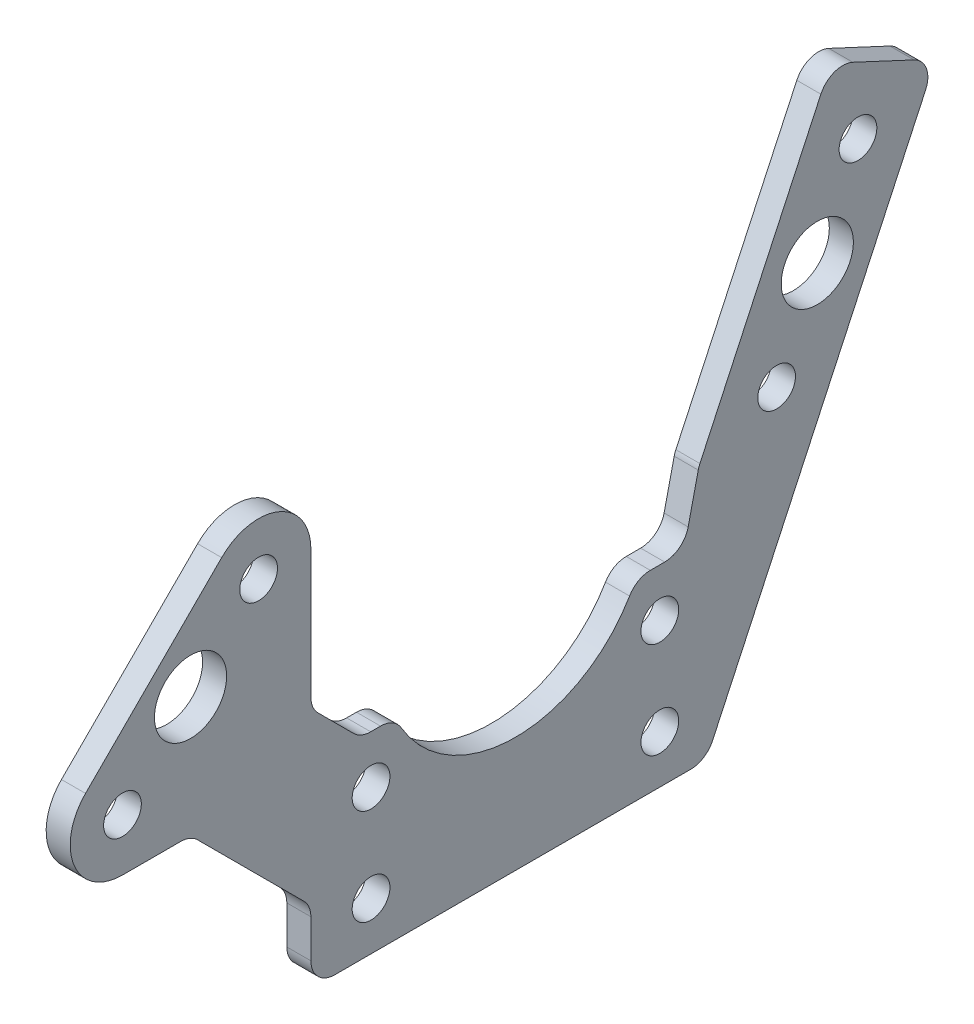
SolidWorks part; units mm, degrees
material "6061-T6 (SS)"
ref_plane "Front Plane" through (0, 0, 0) normal (0, 0, 1) x (1, 0, 0)
ref_plane "Top Plane" through (0, 0, 0) normal (0, 1, 0) x (1, 0, 0)
ref_plane "Right Plane" through (0, 0, 0) normal (1, 0, 0) x (0, 0, -1)
sketch "Sketch1" plane through (0, 0, 0) normal (1, 0, 0) x (0, 0, -1)
  line L1 (0, 0) -> (31.75, 0)
  line L2 (0, 0) -> (0, 31.75)
  line L3 (0, 31.75) -> (31.75, 31.75)
  line L4 (31.75, 0) -> (31.75, 31.75)
  line L8 (6.8947, 6.8947) -> (24.8553, 24.8553) construction
  line L13 (0, 9.7506) -> (21.9994, 31.75)
  line L14 (15.875, 0) -> (31.75, -15.875)
  line L15 (67.7946, 42.0544) -> (85.2585, 27.3883) construction
  line L16 (31.75, 0) -> (84.1375, 0)
  line L17 (31.75, 0) -> (31.75, -25.4)
  line L18 (31.75, -25.4) -> (84.1375, -25.4)
  line L19 (84.1375, 0) -> (84.1375, -25.4)
  line L20 (31.75, 6.5756) -> (38.3256, 0)
  circle A4 centre (39.6875, -6.35) radius 2.4892
  circle A5 centre (77.7875, -6.35) radius 2.4892
  circle A6 centre (39.6875, -19.05) radius 2.4892
  circle A7 centre (77.7875, -19.05) radius 2.4892
  circle A8 centre (15.875, 15.875) radius 4.7625
  arc A9 (42.8625, 0) -> (74.6125, 0) centre (58.7375, 7.2748) ccw
  circle A10 centre (6.8947, 6.8947) radius 2.4892
  circle A11 centre (24.8553, 24.8553) radius 2.4892
  arc A13 (2.0194, 11.7701) -> (6.8947, 0) centre (6.8947, 6.8947) ccw
  arc A14 (31.75, 24.8553) -> (19.9799, 29.7306) centre (24.8553, 24.8553) ccw
  arc A15 (6.8947, 0) -> (11.7701, 11.7701) centre (6.8947, 6.8947) ccw construction
  arc A16 (11.7701, 11.7701) -> (2.0194, 11.7701) centre (6.8947, 6.8947) ccw construction
  arc A17 (19.9799, 19.9799) -> (31.75, 24.8553) centre (24.8553, 24.8553) ccw construction
  arc A18 (19.9799, 29.7306) -> (19.9799, 19.9799) centre (24.8553, 24.8553) ccw construction
  point P8 (15.875, 15.875)
  point P10 (15.875, 31.75)
  point P11 (0, 15.875)
  dimension "D3" = 25.4
  dimension "D5" = 4.9784
  dimension "D10" = 9.525
  dimension "D13" = 17.4625
  dimension "D14" = 45
  dimension "D15" = 25.4
  dimension "D2" = 31.75
  dimension "D4" = 25.4
  dimension "D6" = 52.3875
  dimension "D7" = 6.35
  dimension "D8" = 45
  dimension "D9" = 7.9375
  dimension "D11" = 31.75
  dimension "D12" = 15.875
  dimension "D16" = 6.35
  dimension "D17" = 6.35
extrude "Boss-Extrude1" add sketch "Sketch1" along normal mid plane 3.175
fillet "Fillet1" radius 3.175 9 edges at (0, 6.5756, -31.75) (0, 0, -38.3256) (0, 0, -42.8625) (0, 0, -74.6125) (0, 0, -84.1375) (0, -25.4, -84.1375) (0, -25.4, -31.75) (0, -15.875, -31.75) (0, 0, -15.875)
sketch "Sketch2" plane through (1.5875, 0, 0) normal (1, 0, 0) x (0, 0, -1)
  line L0 (31.75, 50.8) -> (84.1375, 50.8) construction
  line L1 (31.75, -17.1901) -> (31.75, -22.225) construction
  line L2 (84.1375, -3.175) -> (84.1375, -22.225) construction
  line L3 (15.875, 15.875) -> (57.9438, 12.7) construction
  line L5 (31.75, 50.8) -> (31.75, -22.225) construction
  line L6 (98.5614, 24.1048) -> (57.9438, 12.7) construction
  line L7 (82.9335, 8.6213) -> (96.7456, 2.1806)
  line L8 (82.9335, 8.6213) -> (100.3771, 46.0291)
  line L9 (96.7456, 2.1806) -> (114.1892, 39.5884)
  line L10 (100.3771, 46.0291) -> (114.1892, 39.5884)
  line L11 (93.1941, 12.5947) -> (103.9286, 35.6149) construction
  line L12 (98.5614, 24.1048) -> (105.4674, 20.8845) construction
  line L13 (82.9335, 8.6213) -> (80.9625, 0)
  line L14 (96.7456, 2.1806) -> (83.8846, -25.4)
  line L15 (83.8846, -25.4) -> (80.9625, -25.4)
  circle A0 centre (77.7875, -6.35) radius 2.4892 construction
  circle A1 centre (6.8947, 6.8947) radius 2.4892 construction
  circle A2 centre (24.8553, 24.8553) radius 2.4892 construction
  circle A3 centre (15.875, 15.875) radius 4.7625 construction
  circle A4 centre (6.8947, 6.8947) radius 2.4892 construction
  circle A5 centre (24.8553, 24.8553) radius 2.4892 construction
  circle A6 centre (15.875, 15.875) radius 4.7625 construction
  arc A7 (31.75, -22.225) -> (34.925, -25.4) centre (34.925, -22.225) ccw construction
  circle A8 centre (103.9286, 35.6149) radius 2.4892
  circle A9 centre (93.1941, 12.5947) radius 2.4892
  circle A10 centre (98.5614, 24.1048) radius 4.7625
  point P2 (57.9438, 12.7)
  point P6 (57.9438, 50.8)
  point P19 (107.2831, 42.8088)
  point P32 (57.9438, 12.7)
  point P34 (0, 0)
  arc M30 (80.9625, -25.4) -> (84.1375, -22.225) centre (80.9625, -22.225) ccw
  line M31 (84.1375, -22.225) -> (84.1375, -3.175)
  arc M32 (84.1375, -3.175) -> (80.9625, 0) centre (80.9625, -3.175) ccw
  dimension "D1" = 57.15
  dimension "D2" = 38.1
  dimension "D3" = 2
  dimension "D4" = 160
  dimension "D5" = 15.24
  dimension "D6" = 41.275
extrude "Boss-Extrude2" add sketch "Sketch2" against normal up to surface (3.175 mm away) contours L15 L14 L7 L13 M32 M31 M30 | L10 L8 L7 L9 A10 A9 A8
fillet "Fillet2" radius 3.175 5 edges at (0, 8.6213, -82.9335) (0, 46.0291, -100.3771) (0, 39.5884, -114.1892) (0, -25.4, -83.8846) (0, 0, -80.9625)
